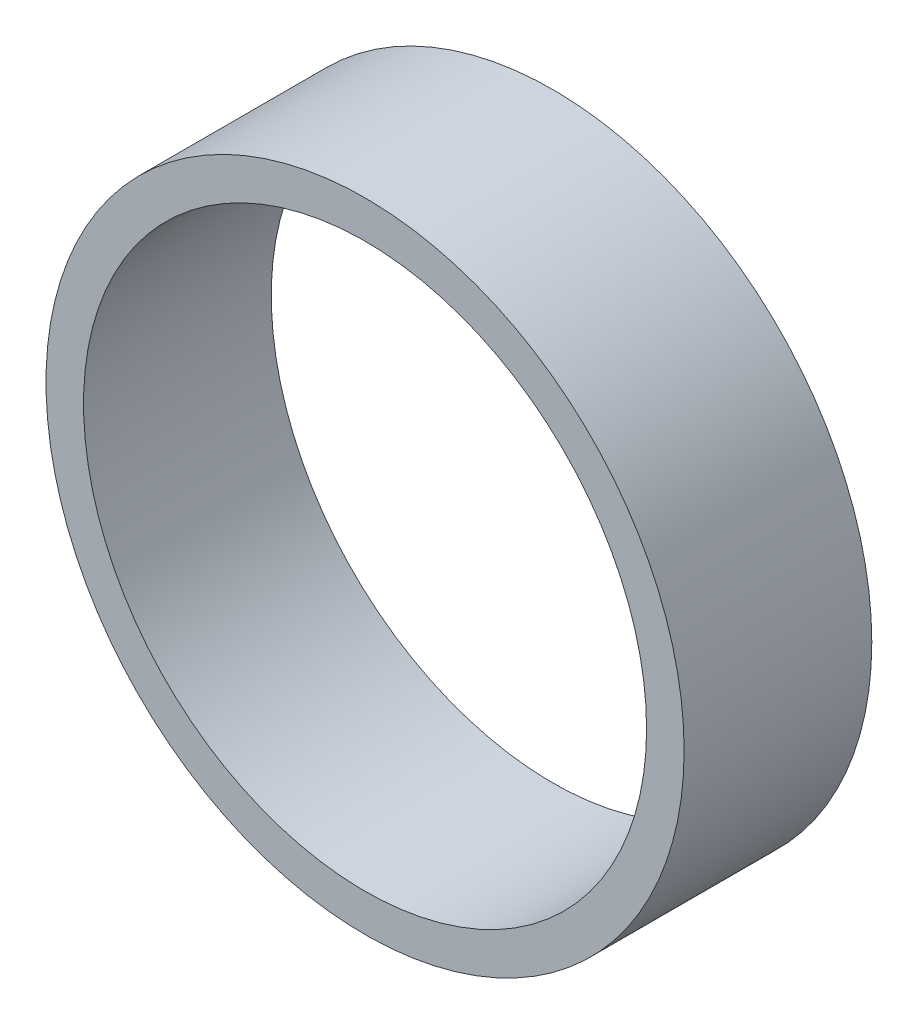
SolidWorks part; units mm, degrees
ref_plane "Plano frontal" through (0, 0, 0) normal (0, 0, 1) x (1, 0, 0)
ref_plane "Plano superior" through (0, 0, 0) normal (0, 1, 0) x (1, 0, 0)
ref_plane "Plano direito" through (0, 0, 0) normal (1, 0, 0) x (0, 0, -1)
sketch "Esboço1" plane through (0, 0, 0) normal (0, 0, 1) x (1, 0, 0)
  circle A0 centre (0, 0) radius 75
  circle A1 centre (0, 0) radius 85
  dimension "D1" = 150
  dimension "D2" = 170
extrude "Ressalto-extrusão2" add sketch "Esboço1" along normal blind 50
